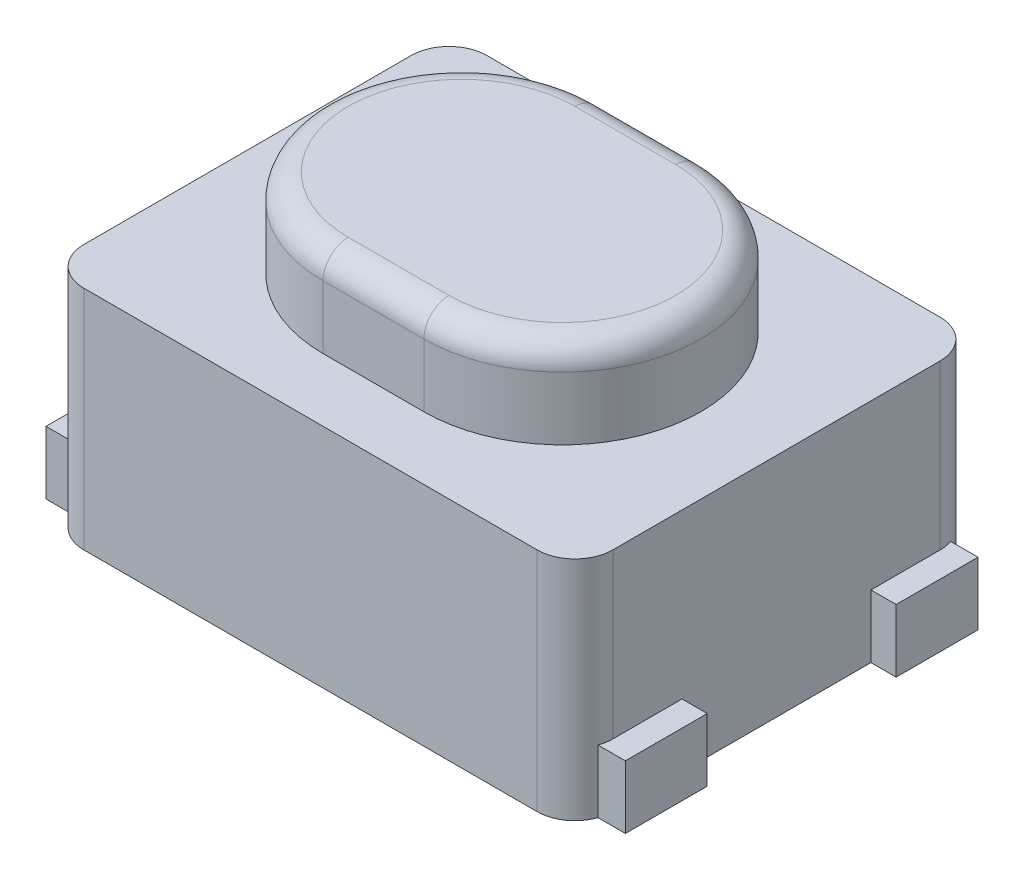
SolidWorks part; units mm, degrees
ref_plane "Front Plane" through (0, 0, 0) normal (0, 0, 1) x (1, 0, 0)
ref_plane "Top Plane" through (0, 0, 0) normal (0, 1, 0) x (1, 0, 0)
ref_plane "Right Plane" through (0, 0, 0) normal (1, 0, 0) x (0, 0, -1)
sketch "Sketch1" plane through (0, 0, 0) normal (0, 1, 0) x (1, 0, 0)
  line L1 (-1.8, 1.6) -> (1.8, 1.6)
  line L2 (-2.1, 1.3) -> (-2.1, -1.3)
  line L3 (-1.8, -1.6) -> (1.8, -1.6)
  line L4 (2.1, 1.3) -> (2.1, -1.3)
  arc A0 (-2.1, -1.3) -> (-1.8, -1.6) centre (-1.8, -1.3) ccw
  arc A1 (1.8, -1.6) -> (2.1, -1.3) centre (1.8, -1.3) ccw
  arc A2 (1.8, 1.6) -> (2.1, 1.3) centre (1.8, 1.3) cw
  arc A3 (-1.8, 1.6) -> (-2.1, 1.3) centre (-1.8, 1.3) ccw
  point P4 (0, 1.6)
  point P5 (2.1, 0)
  point P14 (-2.1, -1.6)
  point P19 (2.1, 1.6)
  point P22 (-2.1, 1.6)
  dimension "D3" = 0.3
  dimension "D1" = 4.2
  dimension "D2" = 3.2
extrude "Boss-Extrude1" add sketch "Sketch1" along normal blind 1.8
sketch "Sketch2" plane through (0, 0, 0) normal (0, 1, 0) x (1, 0, 0)
  line L0 (-0.4, 0) -> (0.4, 0) construction
  line L1 (-0.4, 1.1) -> (0.4, 1.1)
  line L2 (-0.4, -1.1) -> (0.4, -1.1)
  arc A0 (-0.4, 1.1) -> (-0.4, -1.1) centre (-0.4, 0) ccw
  arc A1 (0.4, -1.1) -> (0.4, 1.1) centre (0.4, 0) ccw
  point P3 (0, 0)
  dimension "D2" = 3
  dimension "D1" = 2.2
extrude "Boss-Extrude2" add sketch "Sketch2" along normal blind 2.5
fillet "Fillet1" radius 0.2 4 edges at (0, 2.5, -1.1) (1.5, 2.5, 0) (0, 2.5, 1.1) (-1.5, 2.5, 0)
sketch "Sketch3" plane through (0, 0, 0) normal (0, 1, 0) x (1, 0, 0)
  line L0 (1.925, 0.75) -> (1.925, -0.75) construction
  line L1 (2.3, 0.75) -> (1.55, 0.75)
  line L2 (2.3, 0.75) -> (2.3, 1.4)
  line L3 (2.3, 1.4) -> (1.55, 1.4)
  line L4 (1.55, 0.75) -> (1.55, 1.4)
  line L5 (2.3, -0.75) -> (1.55, -0.75)
  line L6 (2.3, -0.75) -> (2.3, -1.4)
  line L7 (2.3, -1.4) -> (1.55, -1.4)
  line L8 (1.55, -0.75) -> (1.55, -1.4)
  line L9 (0, 1.8353) -> (0, -1.8462) construction
  point P11 (1.925, 0)
  dimension "D1" = 1.5
  dimension "D2" = 2.8
  dimension "D3" = 4.6
  dimension "D4" = 3.1
extrude "Boss-Extrude3" add sketch "Sketch3" along normal blind 0.5
mirror "Mirror1" about plane through (0, 0, 0) normal (1, 0, 0) of "Boss-Extrude3"
